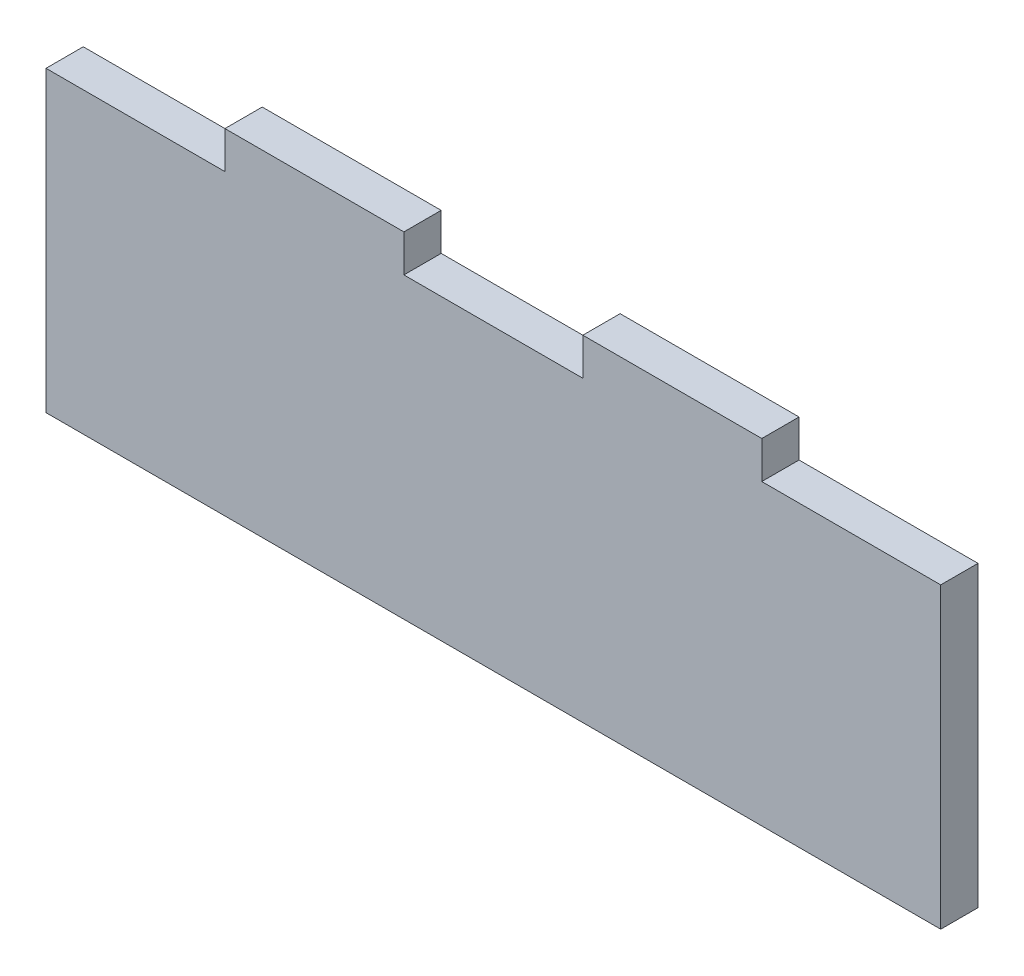
SolidWorks part; units mm, degrees
material "Pine"
ref_plane "Front Plane" through (0, 0, 0) normal (0, 0, 1) x (1, 0, 0)
ref_plane "Top Plane" through (0, 0, 0) normal (0, 1, 0) x (1, 0, 0)
ref_plane "Right Plane" through (0, 0, 0) normal (1, 0, 0) x (0, 0, -1)
sketch "Sketch2" plane through (0, 0, 0) normal (0, 0, 1) x (1, 0, 0)
  line L0 (0, 50.8) -> (0, 0)
  line L1 (0, 0) -> (152.4, 0)
  line L2 (152.4, 0) -> (152.4, 50.8)
  line L3 (152.4, 50.8) -> (121.92, 50.8)
  line L4 (121.92, 50.8) -> (121.92, 57.15)
  line L5 (121.92, 57.15) -> (91.44, 57.15)
  line L6 (91.44, 57.15) -> (91.44, 50.8)
  line L7 (91.44, 50.8) -> (60.96, 50.8)
  line L8 (60.96, 50.8) -> (60.96, 57.15)
  line L9 (60.96, 57.15) -> (30.48, 57.15)
  line L10 (30.48, 57.15) -> (30.48, 50.8)
  line L11 (30.48, 50.8) -> (0, 50.8)
  point P12 (0, 0)
  dimension "D1" = 6.35
  dimension "D2" = 152.4
  dimension "D3" = 30.48
  dimension "D4" = 50.8
extrude "Boss-Extrude1" add sketch "Sketch2" along normal blind 6.35
